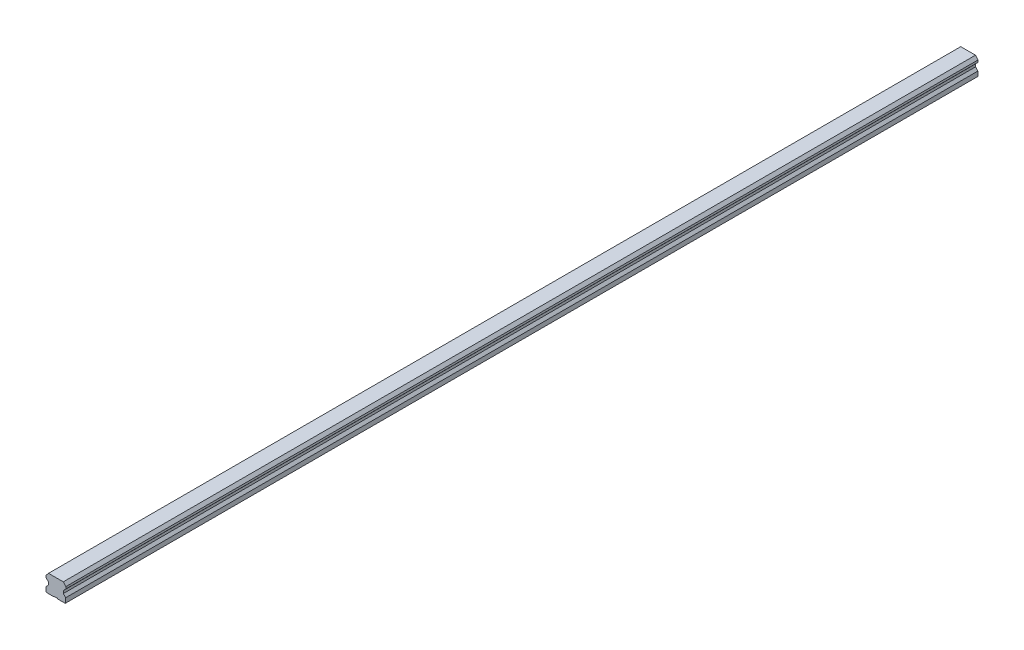
SolidWorks part; units mm, degrees
ref_plane "前视基准面" through (0, 0, 0) normal (0, 0, 1) x (1, 0, 0)
ref_plane "上视基准面" through (0, 0, 0) normal (0, 1, 0) x (1, 0, 0)
ref_plane "右视基准面" through (0, 0, 0) normal (1, 0, 0) x (0, 0, -1)
sketch "草图1" plane through (0, 0, 0) normal (0, 0, 1) x (1, 0, 0)
  line L0 (-87.1056, 0) -> (87.1056, 0) construction
  line L1 (0, 87.1056) -> (0, -87.1056) construction
  line L2 (7.5983, 18.1894) -> (10.1981, 15.2117)
  line L3 (10.1982, 13.0589) -> (7.6925, 10.4386)
  line L4 (10, 5.1652) -> (7.6925, 7.79)
  line L5 (31.5001, 29.5) -> (31.5001, 20.5)
  line L6 (31.0001, 30) -> (31.5001, 29.5)
  line L7 (10, 0.3553) -> (9.6447, 0)
  line L8 (10, 0.3553) -> (10, 5.1652)
  line L9 (23.0001, 5.5) -> (22.5001, 5)
  line L10 (10, 5.0002) -> (22.5001, 5)
  line L11 (23.0001, 5.5) -> (23.0001, 30)
  line L12 (8.4472, 30) -> (8.9472, 29.75)
  line L13 (-8.447, 30) -> (8.4472, 30)
  line L14 (8.9472, 29.75) -> (19.0001, 29.75)
  line L15 (19.5001, 30) -> (19.0001, 29.75)
  line L16 (31.0001, 30) -> (19.5001, 30)
  line L17 (-1.6501, 0.4394) -> (1.6501, 0.4394)
  line L18 (1.6501, 0.4394) -> (2.0009, 0)
  line L19 (-9.6447, 0) -> (-2.0009, 0)
  line L20 (10.1981, 15.2117) -> (10.1982, 13.0589)
  line L21 (7.5983, 18.1894) -> (0, 18.1894)
  line L22 (7.6925, 10.4386) -> (7.6925, 7.79)
  line L23 (-7.5985, 18.1894) -> (-10.1982, 15.2117)
  line L24 (-10.1982, 13.0589) -> (-7.6925, 10.4386)
  line L25 (-10, 5.1652) -> (-7.6925, 7.79)
  line L26 (-31.4999, 29.5) -> (-31.4999, 20.5)
  line L27 (-30.9999, 30) -> (-31.4999, 29.5)
  line L28 (-10, 0.3553) -> (-9.6447, 0)
  line L29 (-10, 0.3553) -> (-10, 5.1652)
  line L30 (-22.9999, 5.5) -> (-22.4999, 5)
  line L31 (-10, 5.0002) -> (-22.4999, 5)
  line L32 (-22.9999, 5.5) -> (-22.9999, 30)
  line L33 (-8.447, 30) -> (-8.947, 29.75)
  line L34 (-8.947, 29.75) -> (-18.9999, 29.75)
  line L35 (-19.4999, 30) -> (-18.9999, 29.75)
  line L36 (-30.9999, 30) -> (-19.4999, 30)
  line L37 (1.6501, 0.4394) -> (-1.6501, 0.4394)
  line L38 (-1.6501, 0.4394) -> (-2.0009, 0)
  line L39 (2.0009, 0) -> (9.6447, 0)
  line L40 (-10.1982, 15.2117) -> (-10.1982, 13.0589)
  line L41 (-7.5985, 18.1894) -> (0, 18.1894)
  line L42 (-7.6925, 10.4386) -> (-7.6925, 7.79)
  line L43 (0, 0.4394) -> (0, 0) construction
  arc A0 (28.633, 17.9037) -> (23.0001, 6.0313) centre (51.9503, -0.4317) ccw
  arc A1 (31.2308, 20.0564) -> (28.633, 17.9037) centre (34.9216, 12.9587) ccw
  arc A2 (31.2308, 20.0564) -> (31.5001, 20.5) centre (31.0001, 20.5) ccw
  arc A3 (-22.9999, 6.0313) -> (-28.6327, 17.9037) centre (-51.9501, -0.4317) ccw
  arc A4 (-28.6327, 17.9037) -> (-31.2306, 20.0564) centre (-34.9214, 12.9587) ccw
  arc A5 (-31.4999, 20.5) -> (-31.2306, 20.0564) centre (-30.9999, 20.5) ccw
  dimension "D1" = 20
extrude "凸台-拉伸1" add sketch "草图1" along normal mid plane 940
